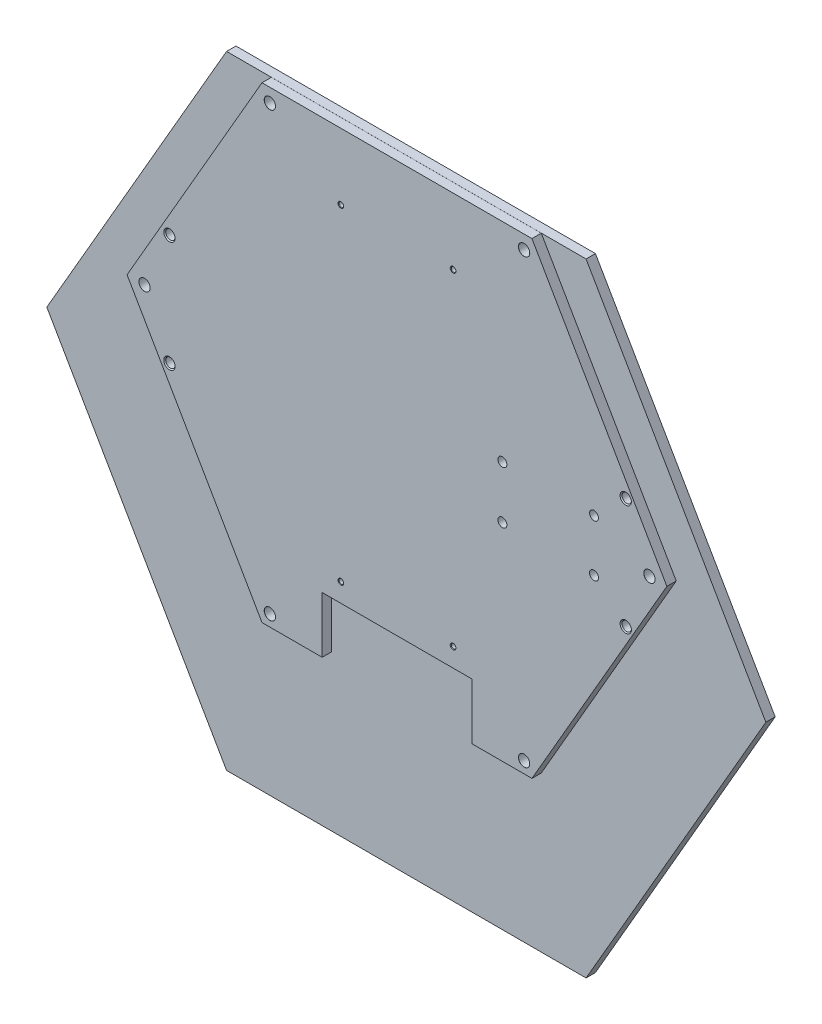
SolidWorks part; units mm, degrees
ref_plane "前视基准面" through (0, 0, 0) normal (0, 0, 1) x (1, 0, 0)
ref_plane "上视基准面" through (0, 0, 0) normal (0, 1, 0) x (1, 0, 0)
ref_plane "右视基准面" through (0, 0, 0) normal (1, 0, 0) x (0, 0, -1)
other "Configuration Table"
sketch "草图8" plane through (0, 0, 0) normal (0, 0, 1) x (1, 0, 0)
  line L0 (0, -95) -> (0, 125) construction
  line L1 (144.3376, 0) -> (72.1688, 125)
  line L2 (72.1688, 125) -> (-72.1688, 125)
  line L3 (-72.1688, 125) -> (-144.3376, 0)
  line L4 (-144.3376, 0) -> (-72.1688, -125)
  line L5 (-72.1688, -125) -> (-40, -125)
  line L6 (72.1688, -125) -> (144.3376, 0)
  line L7 (0, 125) -> (0, -95) construction
  line L8 (-40, -125) -> (-40, -95)
  line L9 (-40, -95) -> (40, -95)
  line L10 (40, -125) -> (40, -95)
  line L11 (40, -125) -> (72.1688, -125)
  arc A0 (40, -118.4272) -> (-40, -118.4272) centre (0, 0) ccw construction
  point P15 (0, -95)
  dimension "D1" = 250
  dimension "D2" = 40
  dimension "D3" = 30
extrude "凸台-拉伸3" add sketch "草图8" along normal blind 5
sketch "草图13" plane through (0, 0, 5) normal (0, 0, 1) x (1, 0, 0)
  line L1 (-40, -95) -> (40, -95) construction
  point P0 (-30, -85)
  dimension "D1" = 30
  dimension "D2" = 10
hole_wizard "M3 螺纹孔1" positions "草图13" profile "草图12" tap size "M3" standard "GB" end condition through all
sketch "草图12" plane through (-30, -85, 5) normal (1, 0, 0) x (0, -1, 0)
  line L0 (0, 0) -> (0, 5)
  line L1 (0, 5) -> (1.25, 5)
  line L2 (1.25, 5) -> (1.25, 0.275)
  line L3 (1.25, 0.275) -> (1.525, 0)
  line L5 (1.525, 0) -> (0, 0)
  line L6 (-1.25, 0.275) -> (-1.525, 0) construction
  line L11 (0, -6.35) -> (0, 107.95) construction
  dimension "通孔螺纹孔钻头直径" = 2.5
  dimension "通孔螺纹孔钻头深度" = 5
  dimension "近端锥形沉头孔直径" = 3.05
  dimension "近端锥形沉头孔角度" = 90
sketch "草图16" plane through (0, 0, 5) normal (0, 0, 1) x (1, 0, 0)
  point P0 (-30, 89.5113)
hole_wizard "M3 螺纹孔2" positions "草图16" profile "草图15" tap size "M3" standard "GB" end condition through all
sketch "草图15" plane through (-30, 89.5113, 5) normal (1, 0, 0) x (0, -1, 0)
  line L0 (0, 0) -> (0, 5)
  line L1 (0, 5) -> (1.25, 5)
  line L2 (1.25, 5) -> (1.25, 0.275)
  line L3 (1.25, 0.275) -> (1.525, 0)
  line L5 (1.525, 0) -> (0, 0)
  line L6 (-1.25, 0.275) -> (-1.525, 0) construction
  line L11 (0, -6.35) -> (0, 107.95) construction
  dimension "通孔螺纹孔钻头直径" = 2.5
  dimension "通孔螺纹孔钻头深度" = 5
  dimension "近端锥形沉头孔直径" = 3.05
  dimension "近端锥形沉头孔角度" = 90
mirror "镜向1" about plane through (0, 0, 0) normal (1, 0, 0) of "M3 螺纹孔2", "M3 螺纹孔1"
sketch "草图19" plane through (0, 0, 5) normal (0, 0, 1) x (1, 0, 0)
  point P0 (-135.0031, 0)
  point P2 (-67.9807, -118.8668)
  point P4 (-67.9807, 117.662)
hole_wizard "Ø6.0 (6) 直径孔1" positions "草图19" profile "草图18" hole size "Ø6.0" standard "GB" end condition through all
sketch "草图18" plane through (-135.0031, 0, 5) normal (1, 0, 0) x (0, -1, 0)
  line L0 (0, 0) -> (0, 5)
  line L1 (0, 5) -> (3, 5)
  line L2 (3, 5) -> (3, 0.025)
  line L3 (3, 0.025) -> (3.025, 0)
  line L5 (3.025, 0) -> (0, 0)
  line L6 (-3, 0.025) -> (-3.025, 0) construction
  line L11 (0, -6.35) -> (0, 107.95) construction
  dimension "通孔孔直径" = 6
  dimension "通孔孔深度" = 5
  dimension "近端锥形沉头孔直径" = 6.05
  dimension "近端锥形沉头孔角度" = 90
mirror "镜向2" about plane through (0, 0, 0) normal (1, 0, 0) of "Ø6.0 (6) 直径孔1"
sketch "草图20" plane through (0, 0, 5) normal (0, 0, 1) x (1, 0, 0)
  circle A0 centre (56.3709, 13.653) radius 2.4
  circle A1 centre (105.3709, 13.3246) radius 2.4
  circle A2 centre (56.3709, -14.347) radius 2.4
  circle A3 centre (105.3709, -14.347) radius 2.4
  dimension "D1" = 4.8
  dimension "D2" = 28
  dimension "D3" = 49
extrude "切除-拉伸2" cut sketch "草图20" against normal through all
sketch "草图21" plane through (0, 0, 5) normal (0, 0, 1) x (1, 0, 0)
  line L2 (192.255, -41.4655) -> (96.1275, 125.0322)
  line L3 (96.1275, 125.0322) -> (-96.1275, 125.0322)
  line L4 (-96.1275, 125.0322) -> (-192.255, -41.4655)
  line L5 (-192.255, -41.4655) -> (-96.1275, -207.9632)
  line L6 (-96.1275, -207.9632) -> (96.1275, -207.9632)
  line L7 (96.1275, -207.9632) -> (192.255, -41.4655)
  circle A1 centre (0, -41.4655) radius 117
  circle A2 centre (0, -126.1254) radius 25
  circle A3 centre (-59.8635, -101.3291) radius 25
  circle A4 centre (-84.6598, -41.4655) radius 25
  circle A5 centre (-59.8635, 18.398) radius 25
  circle A6 centre (0, 43.1943) radius 25
  circle A7 centre (59.8635, 18.398) radius 25
  circle A8 centre (84.6598, -41.4655) radius 25
  circle A9 centre (59.8635, -101.3291) radius 25
  circle A10 centre (0, -41.4655) radius 166.4977 construction
  point P21 (0, -41.4655)
  dimension "D2" = 50
  dimension "D3" = 234
  dimension "D4" = 41.4655
  dimension "D5" = 166.4977
  dimension "D6" = 84.6598
  dimension "D1" = 8
sketch "草图25" plane through (0, 0, 5) normal (0, 0, 1) x (1, 0, 0)
  point P0 (-121.6913, -29.6818)
  point P2 (122.3315, -29.6818)
  point P4 (-121.6913, 29.6483)
  point P6 (122.3315, 29.6483)
hole_wizard "M6 螺纹孔2" positions "草图25" profile "草图24" tap size "M6" standard "GB" end condition up to next
cosmetic thread "孔螺纹线1" parameters "D2"=6
cosmetic thread "孔螺纹线2" parameters "D2"=6
cosmetic thread "孔螺纹线3" parameters "D2"=6
cosmetic thread "孔螺纹线4" parameters "D2"=6
sketch "草图24" plane through (-121.6913, -29.6818, 5) normal (1, 0, 0) x (0, -1, 0)
  line L0 (0, 0) -> (0, 5)
  line L1 (0, 5) -> (2.5, 5)
  line L2 (2.5, 5) -> (2.5, 0.525)
  line L3 (2.5, 0.525) -> (3.025, 0)
  line L5 (3.025, 0) -> (0, 0)
  line L6 (-2.5, 0.525) -> (-3.025, 0) construction
  line L11 (0, -6.35) -> (0, 107.95) construction
  dimension "通孔螺纹孔钻头直径" = 5
  dimension "通孔螺纹孔钻头深度" = 5
  dimension "近端锥形沉头孔直径" = 6.05
  dimension "近端锥形沉头孔角度" = 90
sketch "草图28" plane through (0, 0, 0) normal (0, 0, 1) x (1, 0, 0)
  line L1 (192.255, -41.4655) -> (96.1275, 125.0322)
  line L2 (96.1275, 125.0322) -> (-96.1275, 125.0322)
  line L3 (-96.1275, 125.0322) -> (-192.255, -41.4655)
  line L4 (-192.255, -41.4655) -> (-96.1275, -207.9632)
  line L5 (-96.1275, -207.9632) -> (96.1275, -207.9632)
  line L6 (96.1275, -207.9632) -> (192.255, -41.4655)
  circle A0 centre (0, -41.4655) radius 166.4977 construction
extrude "凸台-拉伸5" add sketch "草图28" against normal blind 5
sketch "草图31" plane through (0, 0, 5) normal (0, 0, 1) x (1, 0, 0)
  point P0 (-121.6913, 29.6483)
  point P3 (-135.0031, 0)
  point P6 (-121.6913, -29.6818)
  point P9 (122.3315, 29.6483)
  point P12 (135.0031, 0)
  point P15 (122.3315, -29.6818)
  point P18 (67.9807, -118.8668)
  point P21 (-67.9807, -118.8668)
  point P24 (67.9807, 117.662)
  point P27 (-67.9807, 117.662)
hole_wizard "M6 螺纹孔3" positions "草图31" profile "草图30" tap size "M6" standard "GB" end condition up to next
sketch "草图30" plane through (-121.6913, 29.6483, 5) normal (1, 0, 0) x (0, -1, 0)
  line L0 (0, 0) -> (0, 10)
  line L1 (0, 10) -> (2.5, 10)
  line L2 (2.5, 10) -> (2.5, 0.525)
  line L3 (2.5, 0.525) -> (3.025, 0)
  line L5 (3.025, 0) -> (0, 0)
  line L6 (-2.5, 0.525) -> (-3.025, 0) construction
  line L11 (0, -6.35) -> (0, 107.95) construction
  dimension "通孔螺纹孔钻头直径" = 5
  dimension "通孔螺纹孔钻头深度" = 10
  dimension "近端锥形沉头孔直径" = 6.05
  dimension "近端锥形沉头孔角度" = 90
cosmetic thread "孔螺纹线5" parameters "D2"=6
cosmetic thread "孔螺纹线6" parameters "D2"=6
cosmetic thread "孔螺纹线7" parameters "D2"=6
cosmetic thread "孔螺纹线8" parameters "D2"=6
cosmetic thread "孔螺纹线9" parameters "D2"=6
cosmetic thread "孔螺纹线10" parameters "D2"=6
cosmetic thread "孔螺纹线11" parameters "D2"=6
cosmetic thread "孔螺纹线12" parameters "D2"=6
cosmetic thread "孔螺纹线13" parameters "D2"=6
cosmetic thread "孔螺纹线14" parameters "D2"=6
